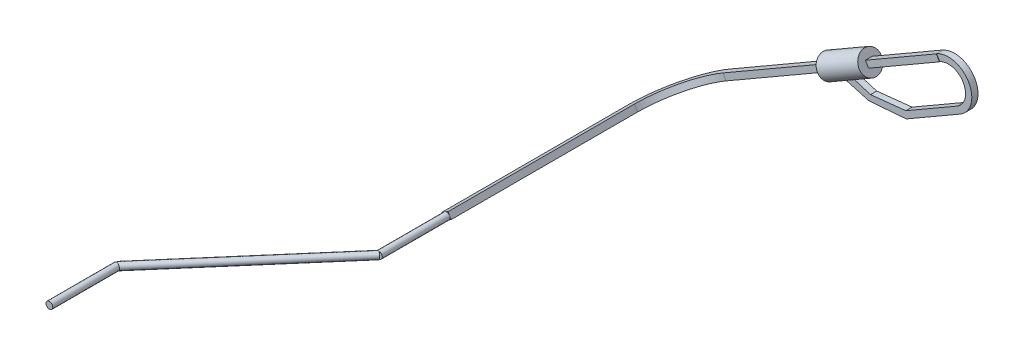
SolidWorks part; units mm, degrees
ref_plane "Front Plane" through (0, 0, 0) normal (0, 0, 1) x (1, 0, 0)
ref_plane "Top Plane" through (0, 0, 0) normal (0, 1, 0) x (1, 0, 0)
ref_plane "Right Plane" through (0, 0, 0) normal (1, 0, 0) x (0, 0, -1)
sketch3d "Plane points - Tendon captive tail"
  point P0 (5.6191, -13.9078, 25.9599)
  point P1 (23.4439, -16.4129, 25.9599)
  point P2 (8.1242, 3.9171, 25.9599)
ref_plane "Drilling plane - Tendon captive tail" through (0, 0, 25.9599) normal (0, 0, 1) x (1, 0, 0)
sketch "S01 - Tendon captive tail" plane through (0, 0, 25.9599) normal (0, 0, 1) x (1, 0, 0)
  circle A0 centre (5.6191, -13.9078) radius 0.6
  dimension "D1" = 1.2
  dimension "D2" = 5.6191
  dimension "D3" = 13.9078
extrude "01 - Tendon captive tail" add sketch "S01 - Tendon captive tail" along normal blind 12
sketch3d "Plane points - Crossed tendon"
  point P0 (25.9808, -15, 0)
  point P1 (25.0166, -32.9742, 0)
  point P2 (40.1158, -15.7582, 11.1187)
ref_plane "Drilling plane - Crossed tendon" through (10.191, -0.5467, -12.9929) normal (-0.6168, 0.0331, 0.7864) x (0.7871, 0.0259, 0.6163)
sketch "S02 - Crossed tendon" plane through (10.191, -0.5467, -12.9929) normal (-0.6168, 0.0331, 0.7864) x (0.7871, 0.0259, 0.6163)
  circle A0 centre (20.0606, -14.9867) radius 0.6
  dimension "D1" = 1.2
  dimension "D2" = 20.0606
  dimension "D3" = 14.9867
extrude "02 - Crossed tendon" add sketch "S02 - Crossed tendon" along normal blind 33.0107
sketch3d "Plane points - Tendon through rear grommet"
  point P0 (25.9808, -15, -12)
  point P1 (43.9808, -15, -12)
  point P2 (25.9808, 3, -12)
ref_plane "Drilling plane - Tendon through rear grommet" through (0, 0, -12) normal (0, 0, 1) x (1, 0, 0)
sketch "S03 - Tendon through rear grommet" plane through (0, 0, -12) normal (0, 0, 1) x (1, 0, 0)
  circle A0 centre (25.9808, -15) radius 0.6
  dimension "D1" = 1.2
  dimension "D2" = 25.9808
  dimension "D3" = 15
extrude "03 - Tendon through rear grommet" add sketch "S03 - Tendon through rear grommet" along normal blind 12
sketch3d "Plane points - Tendon return"
  point P0 (33.775, -10.5, -45)
  point P1 (49.3634, -1.5, -45)
  point P2 (33.775, -10.5, -27)
ref_plane "Drilling plane - Tendon return" through (12.9904, -22.5, 0) normal (0.5, -0.866, 0) x (-0.866, -0.5, 0)
sketch "S04 - Tendon return" plane through (12.9904, -22.5, 0) normal (0.5, -0.866, 0) x (-0.866, -0.5, 0)
  line L0 (-14.4, 12) -> (-14.4, 45)
  line L1 (-24, 54.6) -> (-67.5985, 54.6)
  line L2 (-67.5985, 54.6) -> (-67.5985, 53.4)
  line L3 (-67.5985, 53.4) -> (-24, 53.4)
  line L4 (-15.6, 45) -> (-15.6, 12)
  line L5 (-15.6, 12) -> (-14.4, 12)
  arc A0 (-14.4, 45) -> (-24, 54.6) centre (-24, 45) ccw
  arc A1 (-24, 53.4) -> (-15.6, 45) centre (-24, 45) cw
  dimension "D1" = 9.6
  dimension "D2" = 8.4
  dimension "D3" = 14.4
  dimension "D4" = 67.5985
  dimension "D5" = 12
  dimension "D6" = 53.4
extrude "04 - Tendon return" add sketch "S04 - Tendon return" along normal blind 1.1 from offset 0.55
sketch3d "Plane points - Removable backed eye around polished clevis sleeve"
  point P0 (73.3324, 8.1816, -54)
  point P1 (88.9209, 17.1816, -54)
  point P2 (64.3324, 23.77, -54)
ref_plane "Drilling plane - Removable backed eye around polished clevis sleeve" through (0, 0, -54) normal (0, 0, 1) x (1, 0, 0)
sketch "S05 - Removable backed eye around polished clevis sleeve" plane through (0, 0, -54) normal (0, 0, 1) x (1, 0, 0)
  line L0 (71.0842, 11.6756) -> (71.2574, 11.7756)
  line L1 (75.4074, 4.5876) -> (65.8811, -0.9124)
  line L2 (65.8811, -0.9124) -> (59.26, -1.4443)
  line L3 (59.26, -1.4443) -> (53.7459, 0.1064)
  line L4 (53.7459, 0.1064) -> (54.2119, 1.2993)
  line L5 (54.2119, 1.2993) -> (59.5528, -0.3515)
  line L6 (59.5528, -0.3515) -> (65.8074, 0.3152)
  line L7 (65.8074, 0.3152) -> (74.8574, 5.5402)
  line L8 (71.8074, 10.8229) -> (71.6342, 10.7229)
  line L9 (71.6342, 10.7229) -> (71.0842, 11.6756)
  arc A0 (71.2574, 11.7756) -> (75.4074, 4.5876) centre (73.3324, 8.1816) cw
  arc A1 (74.8574, 5.5402) -> (71.8074, 10.8229) centre (73.3324, 8.1816) ccw
  dimension "D1" = 4.15
  dimension "D2" = 3.05
  dimension "D3" = 53.7459
  dimension "D4" = 54.2119
  dimension "D5" = 59.26
  dimension "D6" = 59.5528
  dimension "D7" = 65.8074
  dimension "D8" = 65.8811
  dimension "D9" = 71.0842
  dimension "D10" = 71.2574
  dimension "D11" = 71.6342
  dimension "D12" = 71.8074
  dimension "D13" = 73.3324
  dimension "D14" = 74.8574
  dimension "D15" = 75.4074
  dimension "D16" = 0.1064
  dimension "D17" = 0.3152
  dimension "D18" = 1.2993
  dimension "D19" = 4.5876
  dimension "D22" = 10.7229
  dimension "D24" = 11.6756
  dimension "D26" = 0.3515
  dimension "D27" = 0.9124
  dimension "D28" = 1.4443
extrude "05 - Removable backed eye around polished clevis sleeve" add sketch "S05 - Removable backed eye around polished clevis sleeve" along normal blind 1.1 from offset 0.55
sketch3d "Plane points - Dressed eye knot envelope"
  point P0 (51.6138, -0.2007, -54)
  point P1 (42.6138, 15.3877, -54)
  point P2 (51.6138, -0.2007, -36)
ref_plane "Drilling plane - Dressed eye knot envelope" through (38.6234, 22.2993, 0) normal (0.866, 0.5, 0) x (0, 0, -1)
sketch "S06 - Dressed eye knot envelope" plane through (38.6234, 22.2993, 0) normal (0.866, 0.5, 0) x (0, 0, -1)
  circle A0 centre (54, -25.9808) radius 2
  dimension "D1" = 4
  dimension "D2" = 54
  dimension "D3" = 25.9808
extrude "06 - Dressed eye knot envelope" add sketch "S06 - Dressed eye knot envelope" along normal blind 8.5
